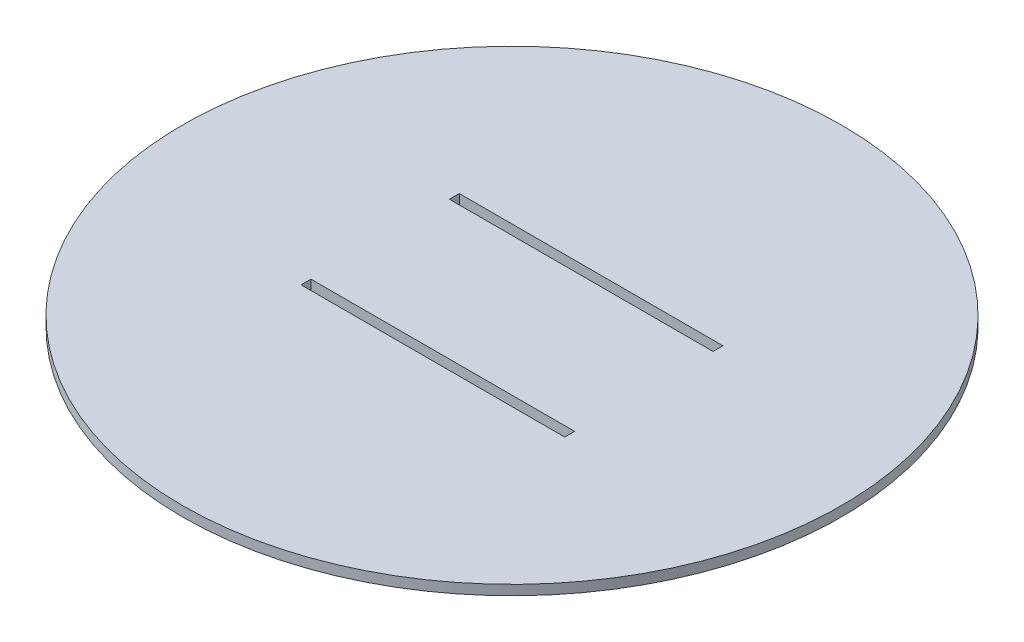
SolidWorks part; units mm, degrees
ref_plane "Front Plane" through (0, 0, 0) normal (0, 0, 1) x (1, 0, 0)
ref_plane "Top Plane" through (0, 0, 0) normal (0, 1, 0) x (1, 0, 0)
ref_plane "Right Plane" through (0, 0, 0) normal (1, 0, 0) x (0, 0, -1)
sketch "Sketch1" plane through (0, 0, 0) normal (0, 1, 0) x (1, 0, 0)
  line L1 (-40, -21) -> (40, -21)
  line L2 (-40, -21) -> (-40, -24)
  line L3 (-40, -24) -> (40, -24)
  line L4 (40, -21) -> (40, -24)
  line L5 (-40, 24) -> (40, 24)
  line L6 (-40, 24) -> (-40, 21)
  line L7 (-40, 21) -> (40, 21)
  line L8 (40, 24) -> (40, 21)
  circle A0 centre (0, 0) radius 100
  dimension "D1" = 3
  dimension "D2" = 80
  dimension "D3" = 3
  dimension "D4" = 80
  dimension "D5" = 40
  dimension "D6" = 40
  dimension "D7" = 42
  dimension "D8" = 21
extrude "Boss-Extrude1" add sketch "Sketch1" along normal blind 3
